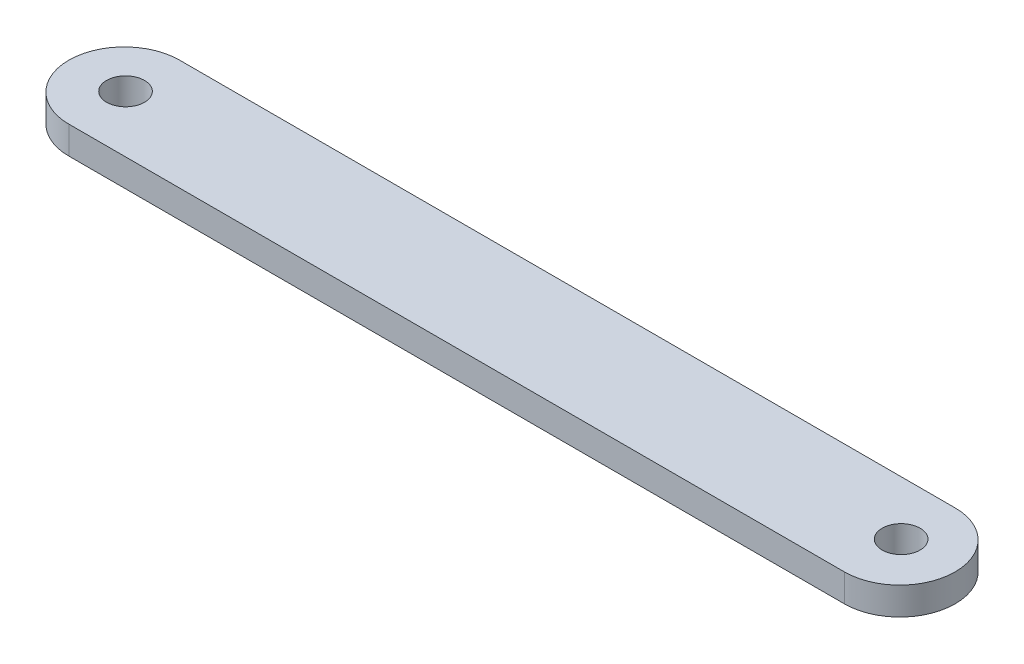
SolidWorks part; units mm, degrees
material "PET"
ref_plane "Front" through (0, 0, 0) normal (0, 0, 1) x (1, 0, 0)
ref_plane "Top" through (0, 0, 0) normal (0, 1, 0) x (1, 0, 0)
ref_plane "Right" through (0, 0, 0) normal (1, 0, 0) x (0, 0, -1)
sketch "Sketch1" plane through (0, 0, 0) normal (0, 1, 0) x (1, 0, 0)
  line L1 (-23.1719, 5.6259) -> (65.7281, 5.6259)
  line L3 (-23.1719, -7.0741) -> (65.7281, -7.0741)
  line L5 (-23.1719, 5.6259) -> (65.7281, -7.0741) construction
  line L6 (-23.1719, -7.0741) -> (65.7281, 5.6259) construction
  arc A0 (-23.1719, 5.6259) -> (-23.1719, -7.0741) centre (-23.1719, -0.7241) ccw
  arc A1 (65.7281, 5.6259) -> (65.7281, -7.0741) centre (65.7281, -0.7241) cw
  point P4 (21.2781, -0.7241)
  dimension "D1" = 6.35
  dimension "D2" = 88.9
extrude "Boss-Extrude1" add sketch "Sketch1" along normal blind 3.175
sketch "Sketch2" plane through (0, 3.175, 0) normal (0, 1, 0) x (1, 0, 0)
  line L0 (-23.1719, -0.5708) -> (40.067, -0.5708) construction
  circle A0 centre (-23.1719, -0.5708) radius 2.175
  circle A2 centre (65.7281, -0.5708) radius 2.175
  dimension "D1" = 4.35
  dimension "D2" = 88.9
  dimension "D3" = 4.35
extrude "Cut-Extrude1" cut sketch "Sketch2" against normal blind 12.7
